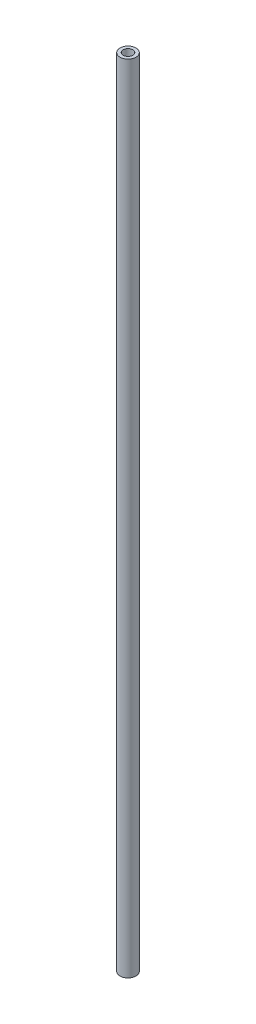
SolidWorks part; units mm, degrees
material "Медь"
ref_plane "Спереди" through (0, 0, 0) normal (0, 0, 1) x (1, 0, 0)
ref_plane "Сверху" through (0, 0, 0) normal (0, 1, 0) x (1, 0, 0)
ref_plane "Справа" through (0, 0, 0) normal (1, 0, 0) x (0, 0, -1)
sketch "Эскиз1" plane through (0, 0, 0) normal (0, 1, 0) x (1, 0, 0)
  circle A0 centre (0, 0) radius 3
  circle A1 centre (0, 0) radius 5
  dimension "D1" = 6
  dimension "D2" = 10
extrude "Бобышка-Вытянуть1" add sketch "Эскиз1" along normal blind 497
